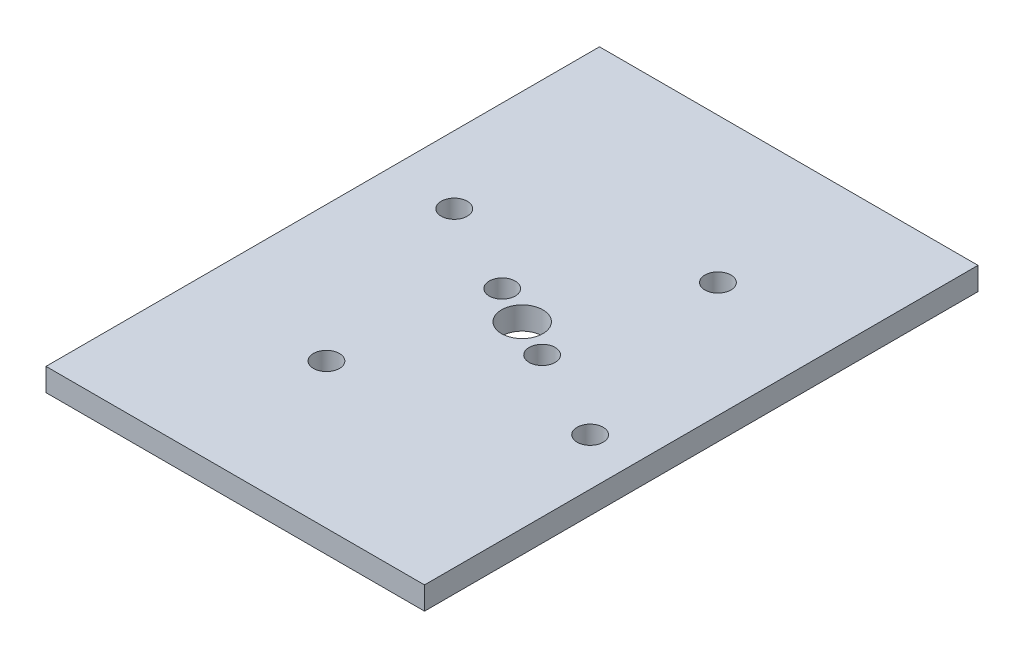
SolidWorks part; units mm, degrees
ref_plane "Спереди" through (0, 0, 0) normal (0, 0, 1) x (1, 0, 0)
ref_plane "Сверху" through (0, 0, 0) normal (0, 1, 0) x (1, 0, 0)
ref_plane "Справа" through (0, 0, 0) normal (1, 0, 0) x (0, 0, -1)
sketch "Эскиз1" plane through (0, 0, 0) normal (0, 1, 0) x (1, 0, 0)
  line L0 (27.5, -42.5) -> (15.5, -42.5) construction
  line L1 (-30.6288, 42.5) -> (27.5, 42.5)
  line L2 (-30.6288, 42.5) -> (-30.6288, -42.5)
  line L3 (-30.6288, -42.5) -> (27.5, -42.5)
  line L4 (27.5, 42.5) -> (27.5, -42.5)
  line L5 (27.5, -42.5) -> (27.5, 42.5) construction
  line L6 (-30.6288, 42.5) -> (-30.6288, -42.5) construction
  circle A0 centre (0, 0) radius 3.175
extrude "Вытянуть1" add sketch "Эскиз1" along normal blind 3.5
sketch "Эскиз2" plane through (0, 3.5, 0) normal (0, 1, 0) x (1, 0, 0)
  circle A0 centre (-5.9458, 2.8819) radius 2
  circle A1 centre (5.9458, -2.8819) radius 2
  circle A2 centre (20.247, -9.8137) radius 2
  circle A3 centre (9.8137, 20.247) radius 2
  circle A4 centre (-9.8137, -20.247) radius 2
  circle A5 centre (-20.247, 9.8137) radius 2
extrude "Вырез-Вытянуть1" cut sketch "Эскиз2" against normal through all
